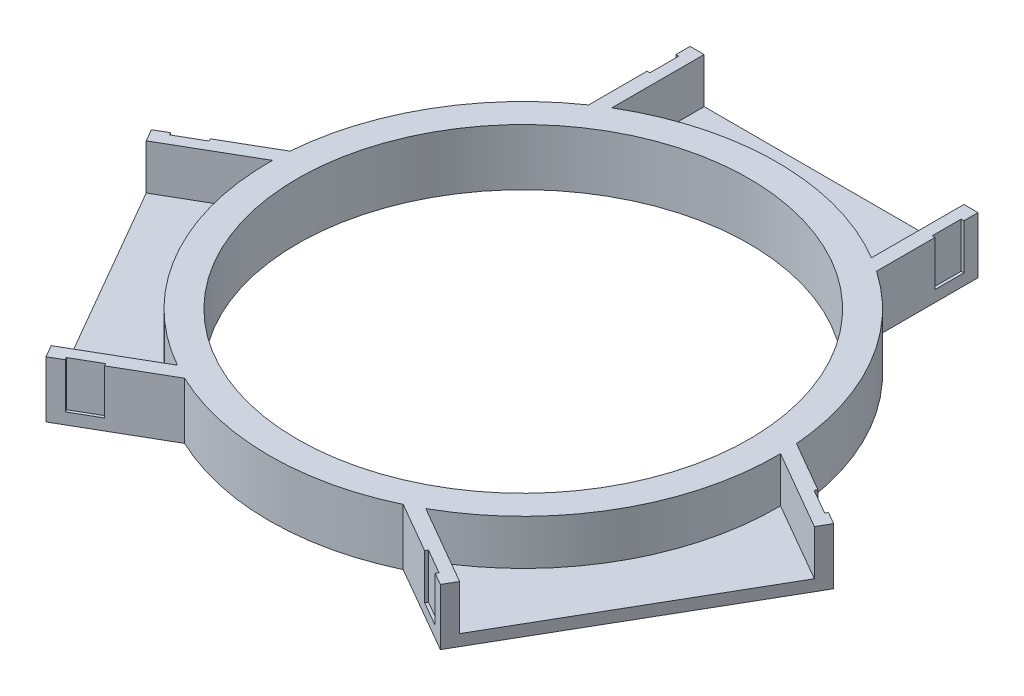
SolidWorks part; units mm, degrees
ref_plane "Front Plane" through (0, 0, 0) normal (0, 0, 1) x (1, 0, 0)
ref_plane "Top Plane" through (0, 0, 0) normal (0, 1, 0) x (1, 0, 0)
ref_plane "Right Plane" through (0, 0, 0) normal (1, 0, 0) x (0, 0, -1)
sketch "Sketch1" plane through (0, 0, 0) normal (0, 1, 0) x (1, 0, 0)
  line L0 (-25.5, 37.0776) -> (-25.5, 47.45)
  line L1 (-25.5, 47.45) -> (-25, 47.45)
  line L2 (-25, 47.45) -> (-25, 52.55)
  line L3 (-25, 52.55) -> (-25.5, 52.55)
  line L4 (-25.5, 52.55) -> (-25.5, 55.05)
  line L5 (-25.5, 55.05) -> (-23, 55.05)
  line L6 (-23, 55.05) -> (-23, 38.6782)
  line L7 (0, 0) -> (0, 45) construction
  line L8 (23, 55.05) -> (23, 38.6782)
  line L9 (25.5, 55.05) -> (23, 55.05)
  line L10 (25.5, 52.55) -> (25.5, 55.05)
  line L11 (25, 52.55) -> (25.5, 52.55)
  line L12 (25, 47.45) -> (25, 52.55)
  line L13 (25.5, 47.45) -> (25, 47.45)
  line L14 (25.5, 37.0776) -> (25.5, 47.45)
  line L15 (58.2596, -4.1914) -> (60.4247, -5.4414)
  line L16 (60.4247, -5.4414) -> (59.1747, -7.6064)
  line L17 (59.1747, -7.6064) -> (44.9963, 0.5795)
  line L18 (58.0096, -4.6244) -> (58.2596, -4.1914)
  line L19 (53.5929, -2.0744) -> (58.0096, -4.6244)
  line L20 (53.8429, -1.6414) -> (53.5929, -2.0744)
  line L21 (44.8602, 3.5448) -> (53.8429, -1.6414)
  line L22 (19.3602, -40.6225) -> (28.3429, -45.8086)
  line L23 (28.3429, -45.8086) -> (28.5929, -45.3756)
  line L24 (28.5929, -45.3756) -> (33.0096, -47.9256)
  line L25 (33.0096, -47.9256) -> (32.7596, -48.3586)
  line L26 (32.7596, -48.3586) -> (34.9247, -49.6086)
  line L27 (34.9247, -49.6086) -> (36.1747, -47.4436)
  line L28 (36.1747, -47.4436) -> (21.9963, -39.2577)
  line L29 (-32.7596, -48.3586) -> (-34.9247, -49.6086)
  line L30 (-34.9247, -49.6086) -> (-36.1747, -47.4436)
  line L31 (-36.1747, -47.4436) -> (-21.9963, -39.2577)
  line L32 (-33.0096, -47.9256) -> (-32.7596, -48.3586)
  line L33 (-28.5929, -45.3756) -> (-33.0096, -47.9256)
  line L34 (-28.3429, -45.8086) -> (-28.5929, -45.3756)
  line L35 (-19.3602, -40.6225) -> (-28.3429, -45.8086)
  line L36 (-44.8602, 3.5448) -> (-53.8429, -1.6414)
  line L37 (-53.8429, -1.6414) -> (-53.5929, -2.0744)
  line L38 (-53.5929, -2.0744) -> (-58.0096, -4.6244)
  line L39 (-58.0096, -4.6244) -> (-58.2596, -4.1914)
  line L40 (-58.2596, -4.1914) -> (-60.4247, -5.4414)
  line L41 (-60.4247, -5.4414) -> (-59.1747, -7.6064)
  line L42 (-59.1747, -7.6064) -> (-44.9963, 0.5795)
  arc A0 (44.8602, 3.5448) -> (25.5, 37.0776) centre (0, 0) ccw
  arc A1 (21.9963, -39.2577) -> (44.9963, 0.5795) centre (0, 0) ccw
  arc A2 (-19.3602, -40.6225) -> (19.3602, -40.6225) centre (0, 0) ccw
  arc A3 (-44.9963, 0.5795) -> (-21.9963, -39.2577) centre (0, 0) ccw
  arc A4 (23, 38.6782) -> (-23, 38.6782) centre (0, 0) ccw
  arc A5 (-25.5, 37.0776) -> (-44.8602, 3.5448) centre (0, 0) ccw
  circle A6 centre (0, 0) radius 40
  point P8 (-25, 50)
  point P21 (25, 50)
  point P57 (0, 0)
  dimension "D7" = 90
  dimension "D9" = 5
  dimension "D1" = 5.1
  dimension "D2" = 0.5
  dimension "D3" = 50
  dimension "D4" = 25
  dimension "D5" = 2
  dimension "D6" = 2.5
  dimension "D8" = 3
extrude "Boss-Extrude1" add sketch "Sketch1" along normal blind 10
sketch "Sketch2" plane through (0, 0, 0) normal (0, -1, 0) x (1, 0, 0)
  line L0 (-60.4247, 5.4414) -> (-34.9247, 49.6086)
  line L1 (-34.9247, 49.6086) -> (-19.3602, 40.6225)
  line L2 (-60.4247, 5.4414) -> (-44.8602, -3.5448)
  line L3 (-25.5, -37.0776) -> (-25.5, -55.05)
  line L4 (-25.5, -55.05) -> (25.5, -55.05)
  line L5 (25.5, -55.05) -> (25.5, -37.0776)
  line L6 (44.8602, -3.5448) -> (60.4247, 5.4414)
  line L7 (60.4247, 5.4414) -> (34.9247, 49.6086)
  line L8 (34.9247, 49.6086) -> (19.3602, 40.6225)
  arc A0 (-44.8602, -3.5448) -> (-25.5, -37.0776) centre (0, 0) ccw construction
  arc A1 (25.5, -37.0776) -> (44.8602, -3.5448) centre (0, 0) ccw construction
  arc A2 (19.3602, 40.6225) -> (-19.3602, 40.6225) centre (0, 0) ccw construction
  arc A3 (-44.8602, -3.5448) -> (-25.5, -37.0776) centre (0, 0) ccw
  arc A4 (25.5, -37.0776) -> (44.8602, -3.5448) centre (0, 0) ccw
  arc A5 (19.3602, 40.6225) -> (-19.3602, 40.6225) centre (0, 0) ccw
  circle A6 centre (0, 0) radius 40 construction
  circle A7 centre (0, 0) radius 40
extrude "Boss-Extrude2" add sketch "Sketch2" against normal blind 2
